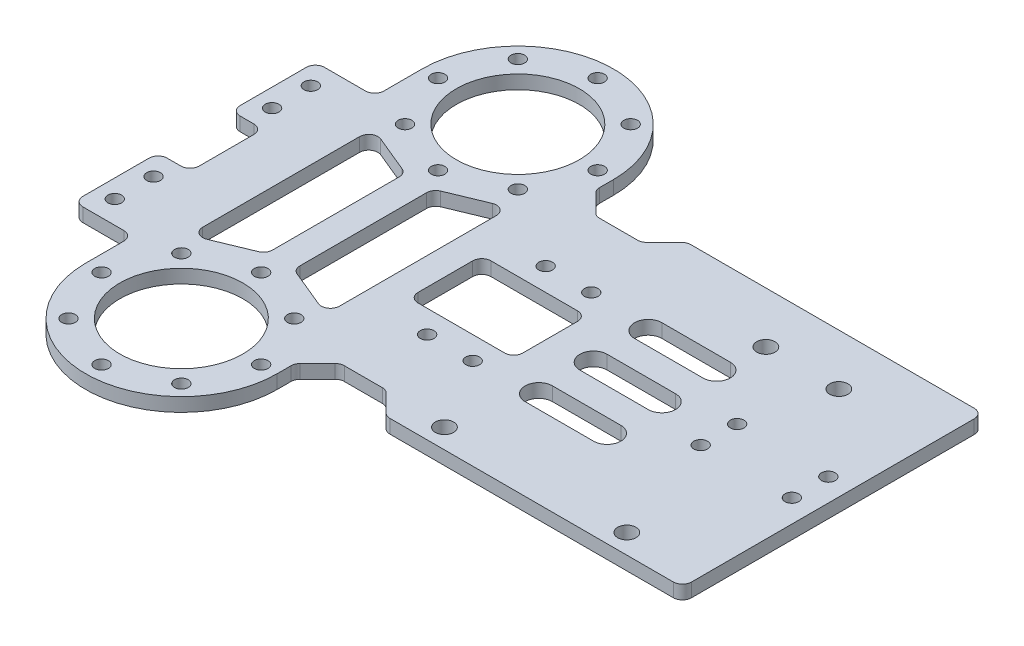
SolidWorks part; units mm, degrees
ref_plane "前视基准面" through (0, 0, 0) normal (0, 0, 1) x (1, 0, 0)
ref_plane "上视基准面" through (0, 0, 0) normal (0, 1, 0) x (1, 0, 0)
ref_plane "右视基准面" through (0, 0, 0) normal (1, 0, 0) x (0, 0, -1)
other "Configuration Table"
sketch "草图1" plane through (0, 0, 0) normal (0, 1, 0) x (1, 0, 0)
  line L0 (0, 0) -> (-50, 0) construction
  line L5 (-30, 60) -> (30, 60)
  line L6 (-30, 60) -> (-30, 30)
  line L7 (-30, -60) -> (30, -60)
  line L8 (30, 60) -> (30, 33)
  line L9 (-30, -30) -> (-30, -60)
  line L10 (-50, 30) -> (-30, 30)
  line L11 (-50, 30) -> (-50, -30)
  line L12 (-50, -30) -> (-30, -30)
  line L13 (130, 33) -> (130, -33)
  line L14 (30, -33) -> (30, -60)
  line L15 (30, 33) -> (130, 33)
  line L16 (30, -33) -> (130, -33)
  line L17 (0, 60) -> (0, -60) construction
  line L18 (0, 0) -> (130, 0) construction
  dimension "D1" = 120
  dimension "D2" = 60
  dimension "D3" = 60
  dimension "D4" = 20
  dimension "D5" = 100
  dimension "D6" = 66
extrude "凸台-拉伸1" add sketch "草图1" along normal blind 3
sketch "草图2" plane through (0, 3, 0) normal (0, 1, 0) x (1, 0, 0)
  line L0 (0, 0) -> (-30, 0) construction
  line L1 (-30, 13) -> (-30, -13) construction
  line L2 (0, 36.9) -> (0, 60) construction
  line L3 (30, 60) -> (-30, 60) construction
  line L4 (0, -36.9) -> (0, -60) construction
  line L5 (-30, 13) -> (-30, 21.5) construction
  line L7 (30, 13) -> (40, 13) construction
  line L13 (30, -13) -> (40, -13) construction
  circle A0 centre (-30, 13) radius 1.5
  circle A1 centre (-30, -13) radius 1.5
  circle A2 centre (0, 36.9) radius 17.5 construction
  circle A5 centre (17.5, 36.9) radius 1.5
  circle A6 centre (12.3744, 24.5256) radius 1.5
  circle A7 centre (0, 19.4) radius 1.5
  circle A8 centre (-12.3744, 24.5256) radius 1.5
  circle A9 centre (-17.5, 36.9) radius 1.5
  circle A10 centre (-12.3744, 49.2744) radius 1.5
  circle A11 centre (0, 54.4) radius 1.5
  circle A12 centre (12.3744, 49.2744) radius 1.5
  circle A13 centre (0, -36.9) radius 17.5 construction
  circle A14 centre (12.3744, -49.2744) radius 1.5
  circle A15 centre (0, -54.4) radius 1.5
  circle A16 centre (-12.3744, -49.2744) radius 1.5
  circle A17 centre (-17.5, -36.9) radius 1.5
  circle A18 centre (-12.3744, -24.5256) radius 1.5
  circle A19 centre (0, -19.4) radius 1.5
  circle A20 centre (12.3744, -24.5256) radius 1.5
  circle A21 centre (17.5, -36.9) radius 1.5
  circle A24 centre (30, 13) radius 1.5
  circle A25 centre (40, 13) radius 1.5
  circle A26 centre (0, 36.9) radius 13.5
  circle A27 centre (0, -36.9) radius 13.5
  circle A28 centre (40, -13) radius 1.5
  circle A29 centre (30, -13) radius 1.5
  circle A30 centre (-30, 21.5) radius 1.5
  circle A32 centre (-30, -21.5) radius 1.5
  point P7 (-30, 0)
  dimension "D2" = 3
  dimension "D3" = 35
  dimension "D5" = 3
  dimension "D9" = 27
  dimension "D11" = 3
  dimension "D14" = 3
  dimension "D1" = 26
  dimension "D6" = 73.8
  dimension "D7" = 30
  dimension "D8" = 10
  dimension "D10" = 30
  dimension "D12" = 13
  dimension "D13" = 43
  dimension "D4" = 8
extrude "通孔" cut sketch "草图2" against normal through all
sketch "草图3" plane through (0, 0, 0) normal (0, 1, 0) x (1, 0, 0)
  line L0 (-21, 36.9) -> (-21, 26.5)
  line L1 (-21, 26.5) -> (-34, 26.5)
  line L6 (-34, 26.5) -> (-34, -26.5)
  line L7 (-34, -26.5) -> (-21, -26.5)
  line L8 (-21, -26.5) -> (-21, -36.9)
  line L9 (21, -36.9) -> (21, -33)
  line L10 (21, -33) -> (106, -33)
  line L11 (106, -33) -> (106, 33)
  line L12 (106, 33) -> (21, 33)
  line L13 (21, 33) -> (21, 36.9)
  line L14 (0, 0) -> (-34, 0) construction
  line L15 (0, 0) -> (106, 0) construction
  line L16 (0, 36.9) -> (0, -36.9) construction
  arc A0 (-21, -36.9) -> (21, -36.9) centre (0, -36.9) ccw
  arc A1 (21, 36.9) -> (-21, 36.9) centre (0, 36.9) ccw
  dimension "D5" = 21
  dimension "D1" = 53
  dimension "D2" = 140
  dimension "D4" = 66
  dimension "D6" = 73.8
  dimension "D8" = 13
extrude "切除-拉伸1" cut sketch "草图3" along normal through all flip side to cut
sketch "草图5" plane through (0, 3, 0) normal (0, 1, 0) x (1, 0, 0)
  line L0 (81, 4) -> (101, 4) construction
  line L1 (106, -33) -> (106, 33) construction
  line L2 (106, 33) -> (21, 33) construction
  line L3 (0, 0) -> (106, 0) construction
  line L4 (69.5, 21.8) -> (85.5, 21.8) construction
  line L5 (49.5, -28.7) -> (89.5, -28.7) construction
  line L6 (21, -33) -> (106, -33) construction
  circle A0 centre (81, 4) radius 1.5
  circle A1 centre (101, 4) radius 1.5
  circle A2 centre (101, -4) radius 1.5
  circle A3 centre (81, -4) radius 1.5
  circle A4 centre (69.5, 21.8) radius 2
  circle A5 centre (85.5, 21.8) radius 2
  circle A6 centre (49.5, -28.7) radius 2
  circle A7 centre (89.5, -28.7) radius 2
  dimension "D3" = 3
  dimension "D5" = 4
  dimension "D8" = 4
  dimension "D1" = 20
  dimension "D2" = 5
  dimension "D4" = 29
  dimension "D6" = 16
  dimension "D7" = 40
  dimension "D9" = 20.5
  dimension "D10" = 11.2
  dimension "D11" = 4.3
  dimension "D12" = 16.5
extrude "切除-拉伸3" cut sketch "草图5" against normal through all
sketch "草图4" plane through (0, 3, 0) normal (0, 1, 0) x (1, 0, 0)
  line L0 (0, 0) -> (-34, 0) construction
  line L13 (-34, 26.5) -> (-34, -26.5) construction
  line L14 (-15, -20.2012) -> (-15, 20.2012)
  line L15 (-34, -8) -> (-34, 8)
  line L16 (-15, 20.2012) -> (-3, 15.2307)
  line L17 (-34, 8) -> (-27, 8)
  line L18 (-3, 15.2307) -> (-3, -15.2307)
  line L19 (-12.3744, 24.5256) -> (0, 19.4) construction
  line L20 (-27, 8) -> (-27, -8)
  line L21 (0, -19.4) -> (0, 19.4) construction
  line L22 (3, 15.2307) -> (3, -15.2307)
  line L23 (15, 20.2012) -> (3, 15.2307)
  line L24 (15, -20.2012) -> (15, 20.2012)
  line L25 (-12.3744, -24.5256) -> (0, -19.4) construction
  line L26 (15, -20.2012) -> (3, -15.2307)
  line L27 (-34, -8) -> (-27, -8)
  line L28 (-15, -20.2012) -> (-3, -15.2307)
  line L29 (21, 33) -> (26, 28)
  line L30 (26, 28) -> (36, 28)
  line L31 (36, 28) -> (41, 33)
  line L32 (106, 33) -> (21, 33) construction
  line L33 (41, 33) -> (21, 33)
  line L34 (31, 33) -> (31, 28) construction
  line L35 (30, 13) -> (40, 13) construction
  line L36 (26, -8) -> (44, -8)
  line L37 (26, -8) -> (26, 8) construction
  line L38 (26, 8) -> (44, 8)
  line L39 (44, -8) -> (44, 8)
  line L40 (26, -8) -> (44, 8) construction
  line L41 (26, 8) -> (44, -8) construction
  line L42 (30, 13) -> (30, -13) construction
  line L43 (35, 0) -> (35, 13) construction
  line L44 (36, -28) -> (41, -33)
  line L45 (26, -28) -> (36, -28)
  line L46 (21, -33) -> (26, -28)
  line L47 (41, -33) -> (21, -33)
  line L48 (61, 0) -> (61, -12) construction
  line L51 (61, 0) -> (61, 33) construction
  line L52 (53.5, 12) -> (68.5, 12) construction
  line L53 (53.5, 15) -> (68.5, 15)
  line L54 (53.5, 9) -> (68.5, 9)
  line L55 (53.5, 0) -> (68.5, 0) construction
  line L56 (53.5, 3) -> (68.5, 3)
  line L57 (53.5, -3) -> (68.5, -3)
  line L58 (53.5, -12) -> (68.5, -12) construction
  line L59 (53.5, -9) -> (68.5, -9)
  line L60 (53.5, -15) -> (68.5, -15)
  line L61 (68.5, 0) -> (106, 0) construction
  line L62 (106, -33) -> (106, 33) construction
  line L63 (26, 8) -> (21, 8)
  line L64 (21, 8) -> (21, -8)
  line L65 (21, -8) -> (26, -8)
  arc A2 (53.5, 15) -> (53.5, 9) centre (53.5, 12) ccw
  arc A3 (68.5, 9) -> (68.5, 15) centre (68.5, 12) ccw
  arc A4 (53.5, 3) -> (53.5, -3) centre (53.5, 0) ccw
  arc A5 (68.5, -3) -> (68.5, 3) centre (68.5, 0) ccw
  arc A6 (53.5, -9) -> (53.5, -15) centre (53.5, -12) ccw
  arc A7 (68.5, -15) -> (68.5, -9) centre (68.5, -12) ccw
  point P23 (15, 0)
  point P24 (3, 0)
  point P25 (-27, 0)
  point P26 (-3, 0)
  point P28 (-15, 0)
  point P38 (35, 0)
  point P68 (61, 12)
  point P75 (61, 0)
  point P82 (61, -12)
  dimension "D14" = 6
  dimension "D13" = 3
  dimension "D1" = 15
  dimension "D2" = 5
  dimension "D3" = 3
  dimension "D4" = 7
  dimension "D5" = 8
  dimension "D6" = 20
  dimension "D7" = 5
  dimension "D8" = 10
  dimension "D9" = 5
  dimension "D10" = 18
  dimension "D11" = 16
  dimension "D12" = 15
  dimension "D15" = 6
  dimension "D16" = 45
  dimension "D17" = 5
extrude "切除-拉伸2" cut sketch "草图4" against normal through all
fillet "圆角1" radius 2 30 edges at (-15, 1.5, -20.2012) (-15, 1.5, 20.2012) (-3, 1.5, 15.2307) (-3, 1.5, -15.2307) (3, 1.5, -15.2307) (3, 1.5, 15.2307) (15, 1.5, 20.2012) (15, 1.5, -20.2012) (44, 1.5, -8) (44, 1.5, 8) (26, 1.5, -28) (36, 1.5, -28) (41, 1.5, -33) (106, 1.5, -33) (106, 1.5, 33) (41, 1.5, 33) (36, 1.5, 28) (26, 1.5, 28) (21, 1.5, 33) (-21, 1.5, 26.5) (-34, 1.5, 8) (-27, 1.5, 8) (-27, 1.5, -8) (-34, 1.5, -8) (-34, 1.5, -26.5) (-21, 1.5, -26.5) (21, 1.5, -33) (-34, 1.5, 26.5) (21, 1.5, 8) (21, 1.5, -8)
